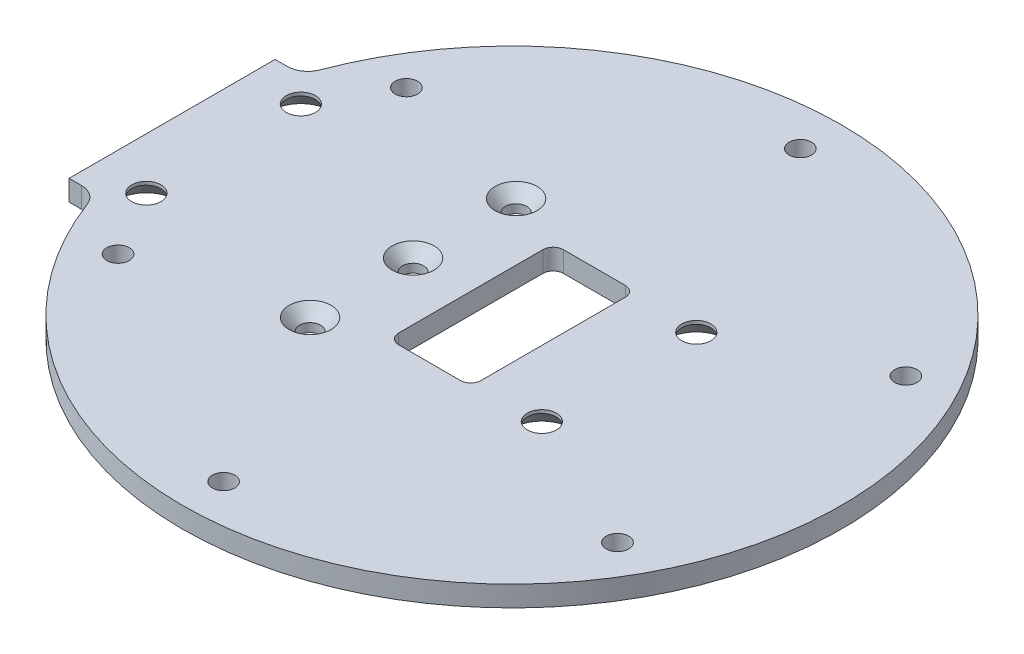
SolidWorks part; units mm, degrees
material "6061-T6 (SS)"
ref_plane "Front Plane" through (0, 0, 0) normal (0, 0, 1) x (1, 0, 0)
ref_plane "Top Plane" through (0, 0, 0) normal (0, 1, 0) x (1, 0, 0)
ref_plane "Right Plane" through (0, 0, 0) normal (1, 0, 0) x (0, 0, -1)
sketch "Sketch1" plane through (0, 0, 0) normal (0, 1, 0) x (1, 0, 0)
  circle A0 centre (0, 0) radius 50.8
  dimension "D1" = 101.6
extrude "Boss-Extrude1" add sketch "Sketch1" along normal blind 3.175
sketch "Sketch8" plane through (0, 0, 0) normal (0, -1, 0) x (1, 0, 0)
  line L1 (-48.2558, -15.875) -> (-52.3875, -15.875)
  line L3 (-48.2558, 15.875) -> (-52.3875, 15.875)
  line L4 (-52.3875, -15.875) -> (-52.3875, 15.875)
  line L5 (-18.5577, -15.875) -> (-52.3875, 15.875) construction
  line L6 (-18.5577, 15.875) -> (-52.3875, -15.875) construction
  circle A0 centre (0, 0) radius 50.8 construction
  circle A1 centre (0, 0) radius 50.8
  point P0 (-35.4726, 0)
  circle M3 centre (0, 0) radius 50.8
  dimension "D1" = 31.75
  dimension "D2" = 52.3875
extrude "Boss-Extrude2" add sketch "Sketch8" against normal up to surface (3.175 mm away) contours L4 L3 M3 | L4 L1 M3
fillet "Fillet1" radius 3.175 2 edges at (-48.2558, 1.5875, -15.875) (-48.2558, 1.5875, 15.875)
hole_wizard "CSK for #8 Flat Head Socket Cap Screw1" positions "Sketch7" profile "Sketch6" countersink size "#8" standard "Ansi Inch" end condition through all
sketch "Sketch7" plane through (0, 0, 0) normal (0, -1, 0) x (1, 0, 0)
  line L2 (0, 0) -> (-50.8, 0) construction
  circle A0 centre (0, 0) radius 50.8 construction
  point P0 (-44.45, 11.9062)
  point P1 (-44.45, -11.9063)
  point P22 (16.51, -11.9063)
  point P24 (16.51, 11.9062)
  dimension "D1" = 23.8125
  dimension "D2" = 11.9062
  dimension "D3" = 6.35
  dimension "D4" = 60.96
sketch "Sketch6" plane through (-44.45, 0, 11.9062) normal (1, 0, 0) x (0, 0, -1)
  line L0 (0, 0) -> (0, 3.175)
  line L1 (0, 3.175) -> (2.2479, 3.175)
  line L2 (2.2479, 3.175) -> (2.2479, 2.659)
  line L3 (2.2479, 2.659) -> (4.5593, 0)
  line L5 (4.5593, 0) -> (0, 0)
  line L6 (-2.2479, 2.659) -> (-4.5593, 0) construction
  line L11 (0, -6.35) -> (0, 107.95) construction
  dimension "Thru Hole Dia." = 4.4958
  dimension "Thru Hole Depth" = 3.175
  dimension "Near C'Sink Dia." = 9.1186
  dimension "Near C'Sink Angle" = 82
hole_wizard "#8-32 Tapped Hole1" positions "Sketch11" profile "Sketch10" tap size "#8-32" standard "Ansi Inch"
sketch "Sketch11" plane through (0, 3.175, 0) normal (0, 1, 0) x (-1, 0, 0)
  point P0 (0, -44.45)
  dimension "D1" = 44.45
sketch "Sketch10" plane through (0, 3.175, -44.45) normal (1, 0, 0) x (0, 0, 1)
  line L0 (0, 0) -> (0, 11.7058)
  line L1 (0, 11.7058) -> (1.7272, 10.668)
  line L2 (1.7272, 10.668) -> (1.7272, 0)
  line L5 (1.7272, 0) -> (0, 0)
  line L10 (0, 11.7058) -> (-1.7272, 10.668) construction
  line L11 (0, -6.35) -> (0, 107.95) construction
  dimension "Tap Drill Dia." = 3.4544
  dimension "Tap Drill Depth" = 10.668
  dimension "Drill Angle" = 118
pattern_circular "CirPattern1" count 6 over 360 about axis through (0, 0, 0) along (0, 1, 0) of "#8-32 Tapped Hole1"
hole_wizard "CSK for #4 Flat Head Socket Cap Screw2" positions "Sketch16" profile "Sketch15" countersink size "#4" standard "Ansi Inch" end condition through all
sketch "Sketch16" plane through (0, 3.175, 0) normal (0, 1, 0) x (-1, 0, 0)
  point P0 (15.24, 0)
  point P1 (15.24, -15.875)
  point P3 (15.24, 15.875)
  dimension "D1" = 15.875
  dimension "D2" = 15.875
  dimension "D3" = 15.24
sketch "Sketch15" plane through (-15.24, 3.175, 0) normal (1, 0, 0) x (0, 0, 1)
  line L0 (0, 0) -> (0, 3.175)
  line L1 (0, 3.175) -> (1.6319, 3.175)
  line L2 (1.6319, 3.175) -> (1.6319, 1.8481)
  line L3 (1.6319, 1.8481) -> (3.2385, 0)
  line L5 (3.2385, 0) -> (0, 0)
  line L6 (-1.6319, 1.8481) -> (-3.2385, 0) construction
  line L11 (0, -6.35) -> (0, 107.95) construction
  dimension "Thru Hole Dia." = 3.2639
  dimension "Thru Hole Depth" = 3.175
  dimension "Near C'Sink Dia." = 6.477
  dimension "Near C'Sink Angle" = 82
sketch "Sketch17" plane through (0, 3.175, 0) normal (0, 1, 0) x (1, 0, 0)
  line L1 (6.35, 12.7) -> (-6.35, 12.7)
  line L2 (6.35, 12.7) -> (6.35, -12.7)
  line L3 (6.35, -12.7) -> (-6.35, -12.7)
  line L4 (-6.35, 12.7) -> (-6.35, -12.7)
  line L5 (6.35, 12.7) -> (-6.35, -12.7) construction
  line L6 (6.35, -12.7) -> (-6.35, 12.7) construction
  point P0 (0, 0)
  dimension "D1" = 25.4
  dimension "D2" = 12.7
extrude "Cut-Extrude2" cut sketch "Sketch17" against normal through all
fillet "Fillet2" radius 1.5875 4 edges at (-6.35, 1.5875, -12.7) (6.35, 1.5875, -12.7) (-6.35, 1.5875, 12.7) (6.35, 1.5875, 12.7)
